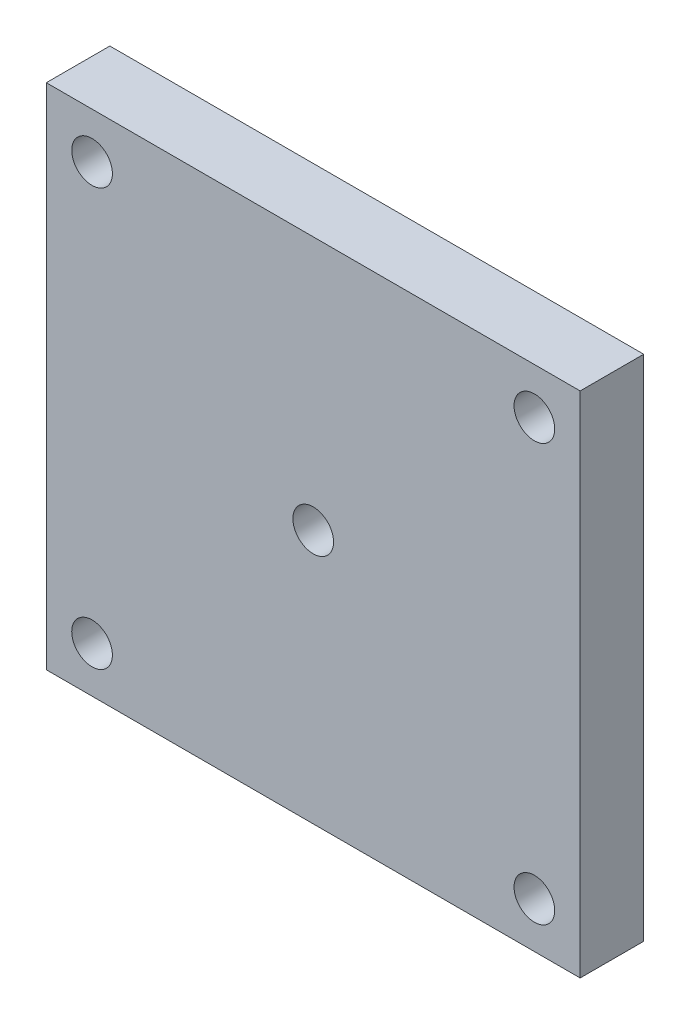
SolidWorks part; units mm, degrees
ref_plane "Top Plane" through (0, 0, 0) normal (0, 0, 1) x (1, 0, 0)
ref_plane "Right Plane" through (0, 0, 0) normal (0, 1, 0) x (1, 0, 0)
ref_plane "Front Plane" through (0, 0, 0) normal (1, 0, 0) x (0, 0, -1)
sketch "Sketch1" plane through (0, 0, 0) normal (0, 0, 1) x (1, 0, 0)
  line L0 (-21, 20) -> (21, -20) construction
  line L1 (-21, 20) -> (21, 20)
  line L2 (-21, 20) -> (-21, -20)
  line L3 (-21, -20) -> (21, -20)
  line L4 (21, 20) -> (21, -20)
  dimension "D1" = 42
  dimension "D2" = 40
extrude "Boss-Extrude1" add sketch "Sketch1" along normal mid plane 5
sketch "Sketch2" plane through (0, 0, 2.5) normal (0, 0, 1) x (1, 0, 0)
  line L0 (0, 20) -> (0, -20) construction
  line L1 (21, 20) -> (-21, 20) construction
  line L2 (-21, -20) -> (21, -20) construction
  line L3 (-21, 0) -> (21, 0) construction
  line L4 (-21, 20) -> (-21, -20) construction
  line L5 (21, -20) -> (21, 20) construction
  circle A0 centre (-17.4, 16.4) radius 1.6
  circle A1 centre (17.4, 16.4) radius 1.6
  circle A2 centre (17.4, -16.4) radius 1.6
  circle A3 centre (-17.4, -16.4) radius 1.6
  circle A4 centre (0, 0) radius 1.6
  dimension "D1" = 3.2
  dimension "D2" = 2
  dimension "D3" = 2
extrude "Cut-Extrude1" cut sketch "Sketch2" against normal through all
